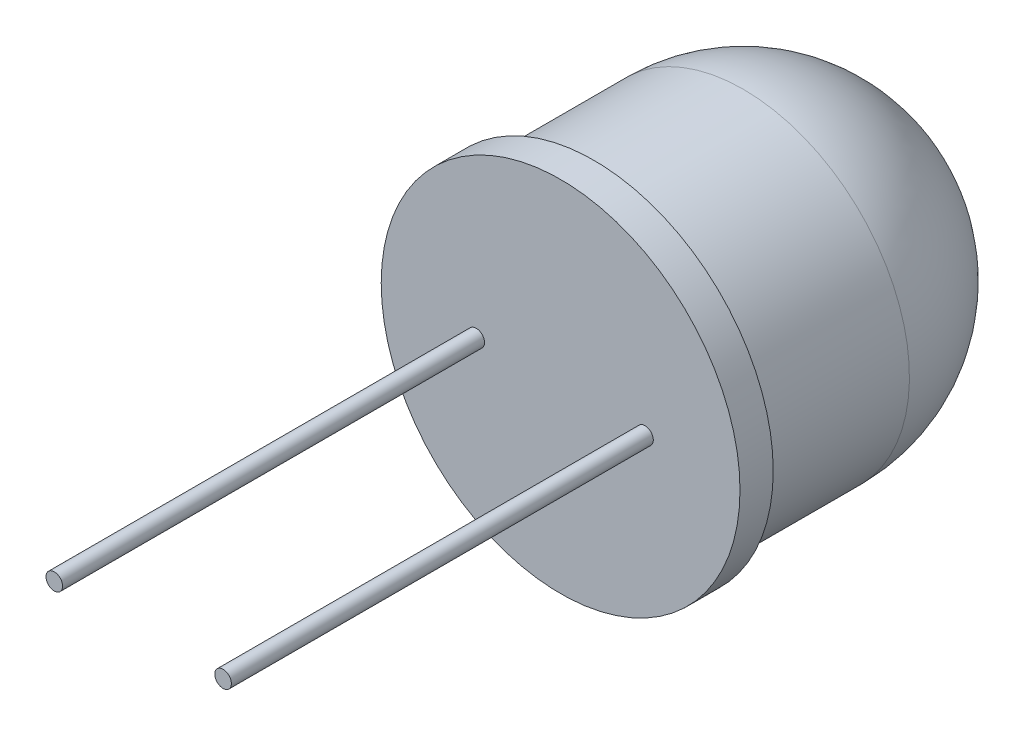
SolidWorks part; units mm, degrees
ref_plane "前视基准面" through (0, 0, 0) normal (0, 0, 1) x (1, 0, 0)
ref_plane "上视基准面" through (0, 0, 0) normal (0, 1, 0) x (1, 0, 0)
ref_plane "右视基准面" through (0, 0, 0) normal (1, 0, 0) x (0, 0, -1)
sketch "草图1" plane through (0, 0, 0) normal (0, 0, 1) x (1, 0, 0)
  circle A0 centre (0, 0) radius 5
  dimension "D1" = 10
extrude "拉伸1" add sketch "草图1" along normal blind 5.5
sketch "草图2" plane through (0, 0, 5.5) normal (0, 0, 1) x (1, 0, 0)
  circle A0 centre (0, 0) radius 5.4
  dimension "D1" = 10.8
extrude "拉伸2" add sketch "草图2" against normal blind 1
sketch "草图3" plane through (0, 0, 5.5) normal (0, 0, -1) x (-1, 0, 0)
  line L0 (0, 2.011) -> (0, -2.1052) construction
  line L1 (-2.1813, 0) -> (2.3335, 0) construction
  circle A0 centre (-2.54, 0) radius 0.25
  circle A1 centre (2.54, 0) radius 0.25
  dimension "D1" = 0.5
  dimension "D2" = 5.08
extrude "拉伸3" add sketch "草图3" against normal blind 12.7
sketch "草图5" plane through (0, 0, 0) normal (1, 0, 0) x (0, 0, -1)
  line L0 (0, 5) -> (0, 0)
  line L1 (5, 0) -> (0, 0)
  arc A0 (0, 5) -> (5, 0) centre (0, 0) cw
  dimension "D1" = 5
revolve "旋转2" add sketch "草图5" angle 360 about L1
